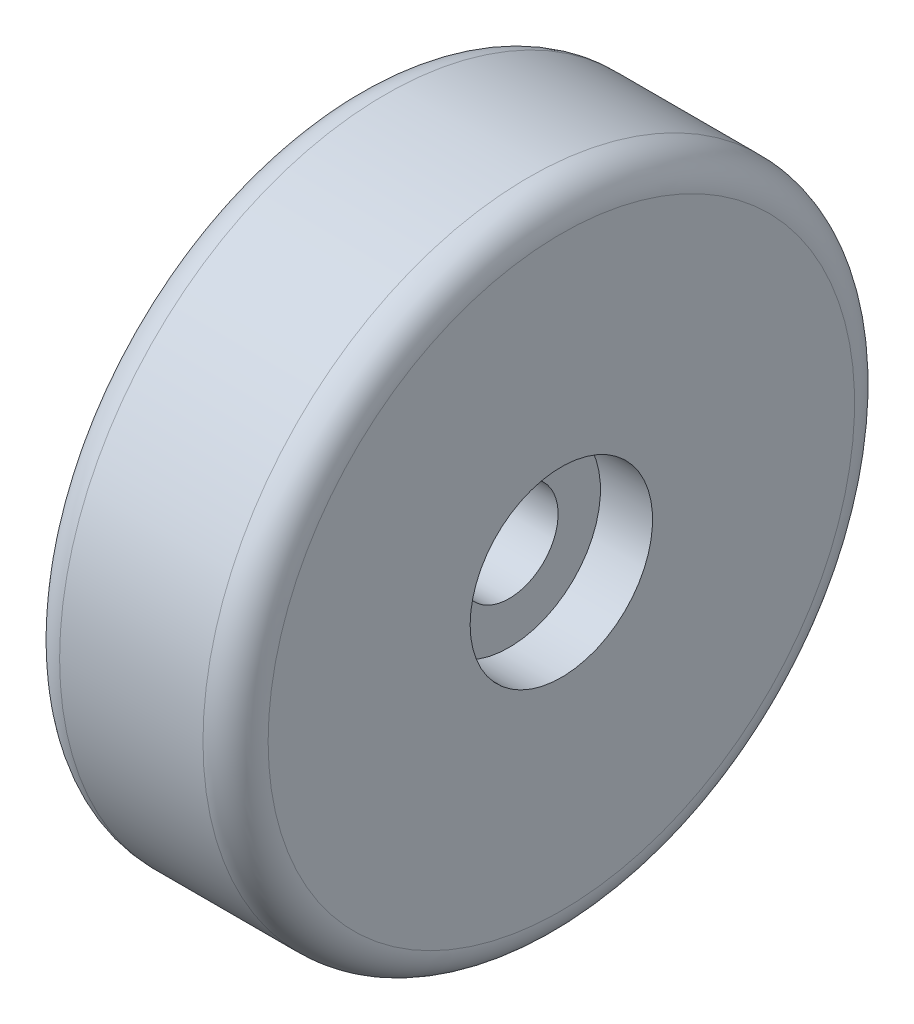
SolidWorks part; units mm, degrees
ref_plane "Front Plane" through (0, 0, 0) normal (0, 0, 1) x (1, 0, 0)
ref_plane "Top Plane" through (0, 0, 0) normal (0, 1, 0) x (1, 0, 0)
ref_plane "Right Plane" through (0, 0, 0) normal (1, 0, 0) x (0, 0, -1)
sketch "Sketch1" plane through (0, 0, 0) normal (0, 0, 1) x (1, 0, 0)
  line L0 (0, 0) -> (0, -32221.1903) construction
  line L1 (0, 0) -> (32221.1903, 0) construction
  line L2 (8, 7.5) -> (-8, 7.5)
  line L3 (-8, 7.5) -> (-8, 14)
  line L4 (-8, 14) -> (-16, 14)
  line L5 (-16, 14) -> (-16, 50)
  line L6 (-16, 50) -> (16, 50)
  line L7 (16, 14) -> (16, 50)
  line L8 (8, 14) -> (16, 14)
  line L9 (8, 7.5) -> (8, 14)
  point P8 (0, 7.5)
  point P13 (0, 50)
  dimension "D1" = 32
  dimension "D2" = 100
  dimension "D3" = 15
  dimension "D4" = 28
  dimension "D5" = 16
revolve "Revolve1" add sketch "Sketch1" angle 360 about L1
fillet "Fillet1" radius 5 2 edges at (-16, 0, 50) (16, 0, 50)
